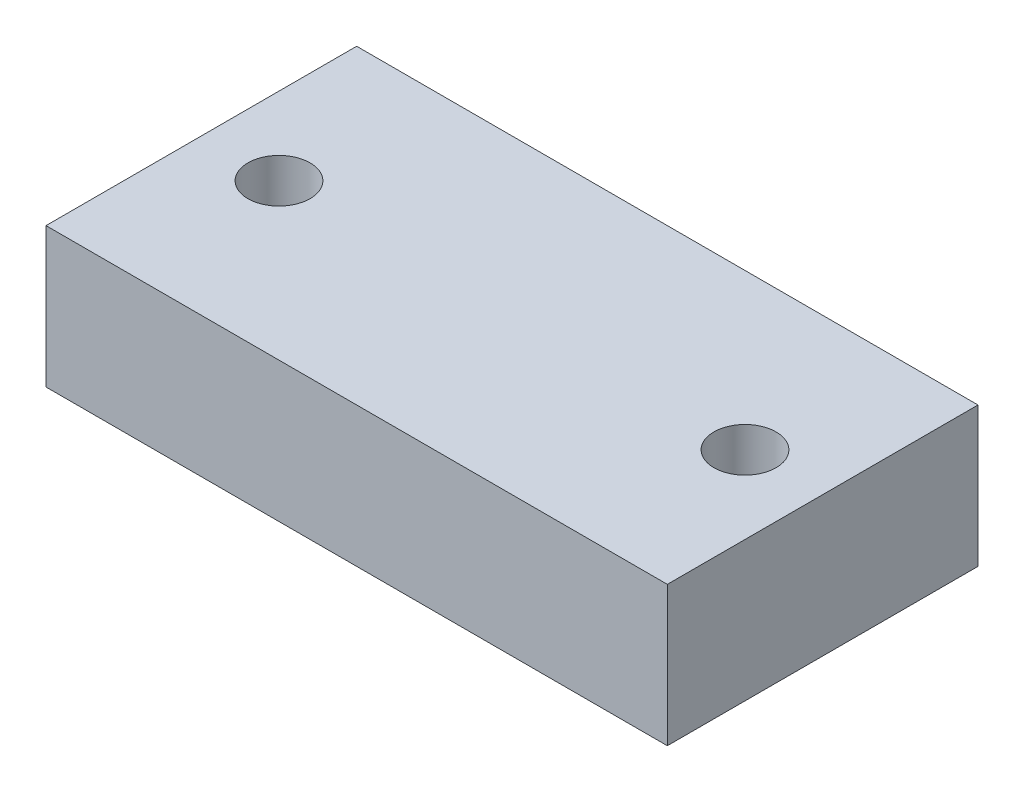
SolidWorks part; units mm, degrees
ref_plane "Front Plane" through (0, 0, 0) normal (0, 0, 1) x (1, 0, 0)
ref_plane "Top Plane" through (0, 0, 0) normal (0, 1, 0) x (1, 0, 0)
ref_plane "Right Plane" through (0, 0, 0) normal (1, 0, 0) x (0, 0, -1)
sketch "Sketch1" plane through (0, 0, 0) normal (0, 1, 0) x (1, 0, 0)
  line L0 (0, 20) -> (0, -20) construction
  line L1 (-40, -20) -> (40, -20)
  line L2 (-40, -20) -> (-40, 20)
  line L3 (-40, 20) -> (40, 20)
  line L4 (40, -20) -> (40, 20)
  line L5 (-40, -20) -> (40, 20) construction
  line L6 (-40, 20) -> (40, -20) construction
  line L7 (-40, 0) -> (40, 0) construction
  circle A1 centre (30, 0) radius 4
  circle A2 centre (-30, 0) radius 4
  point P0 (0, 0)
  dimension "D3" = 8
  dimension "D5" = 8
  dimension "D1" = 80
  dimension "D2" = 40
  dimension "D4" = 10
  dimension "D6" = 10
extrude "Boss-Extrude1" add sketch "Sketch1" along normal blind 18
equation "\"Case_Width\" = 790mm"
equation "\"Case_Depth\" = 470mm"
equation "\"Tank_Width\" = 660mm"
equation "\"WoodSheet_Thickness\" = 18mm"
equation "\"D1@Boss-Extrude1\"=\"WoodSheet_Thickness\""
